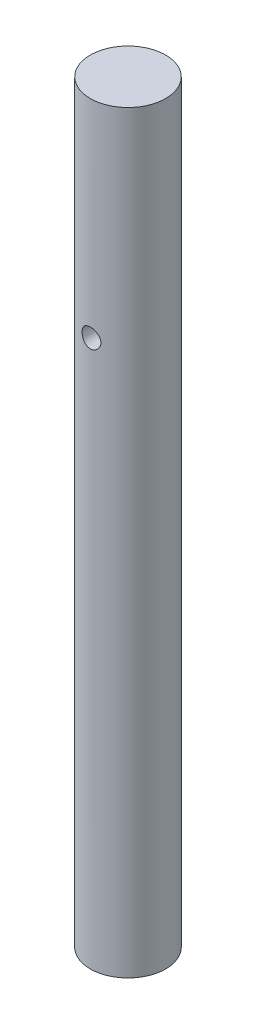
SolidWorks part; units mm, degrees
ref_plane "Front Plane" through (0, 0, 0) normal (0, 0, 1) x (1, 0, 0)
ref_plane "Top Plane" through (0, 0, 0) normal (0, 1, 0) x (1, 0, 0)
ref_plane "Right Plane" through (0, 0, 0) normal (1, 0, 0) x (0, 0, -1)
sketch "Sketch1" plane through (0, 0, 0) normal (0, 1, 0) x (1, 0, 0)
  circle A0 centre (0, 0) radius 40
  dimension "D1" = 80
extrude "Boss-Extrude1" add sketch "Sketch1" along normal blind 800
sketch "Sketch2" plane through (0, 0, 0) normal (0, 0, 1) x (1, 0, 0)
  line L0 (0, 800) -> (0, 0) construction
  line L1 (40, 800) -> (-40, 800) construction
  circle A0 centre (0, 580) radius 10
  dimension "D1" = 20
  dimension "D2" = 220
extrude "Cut-Extrude1" cut sketch "Sketch2" against normal mid plane 800
